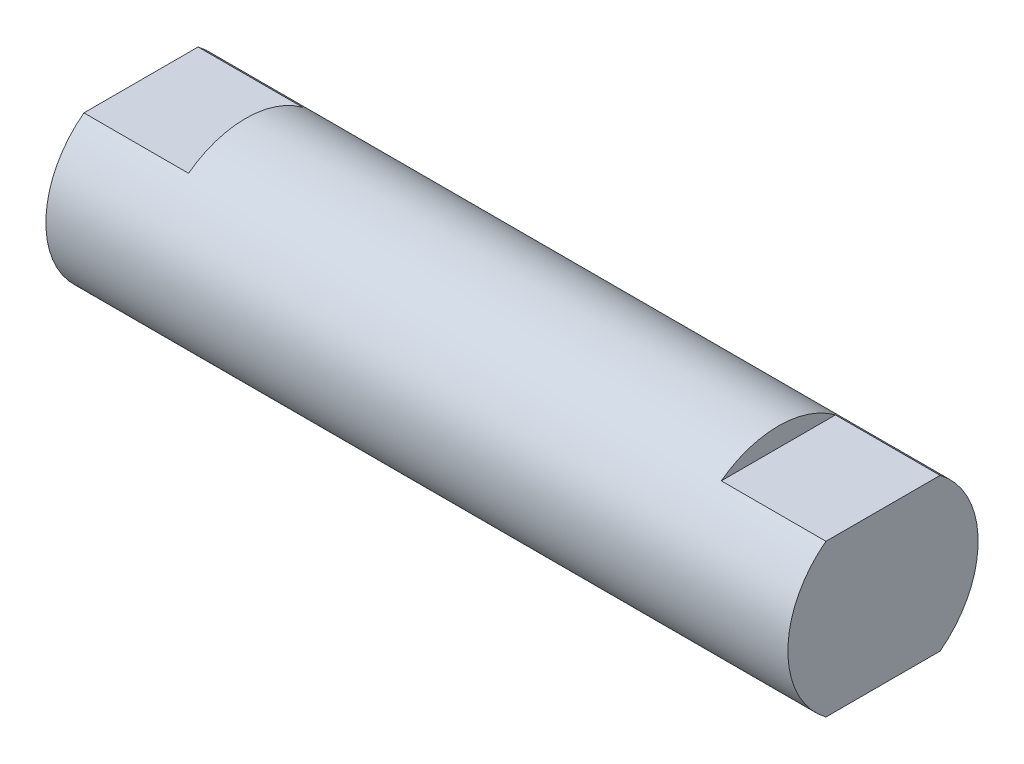
SolidWorks part; units mm, degrees
ref_plane "Front" through (0, 0, 0) normal (0, 0, 1) x (1, 0, 0)
ref_plane "Top" through (0, 0, 0) normal (0, 1, 0) x (1, 0, 0)
ref_plane "Right" through (0, 0, 0) normal (1, 0, 0) x (0, 0, -1)
ref_plane "Plane1" through (9.75, 0, 0) normal (1, 0, 0) x (0, 0, -1)
sketch "Sketch1" plane through (0, 0, 0) normal (1, 0, 0) x (0, 0, -1)
  circle A0 centre (0, 0) radius 2.5
  dimension "D1" = 5
extrude "Boss-Extrude1" add sketch "Sketch1" against normal mid plane 19.5
sketch "Sketch2" plane through (-9.75, 0, 0) normal (-1, 0, 0) x (0, 0, 1)
  line L0 (-1.5, 2) -> (1.5, 2)
  line L1 (1.5, -2) -> (-1.5, -2)
  line L2 (0, 0) -> (1.5, 0) construction
  arc A0 (1.5, 2) -> (-1.5, 2) centre (0, 0) ccw
  arc A1 (-1.5, -2) -> (1.5, -2) centre (0, 0) ccw
  circle A2 centre (0, 0) radius 2.5 construction
  dimension "D1" = 4
extrude "Cut-Extrude1" cut sketch "Sketch2" against normal blind 2.75
mirror "Mirror1" about plane through (0, 0, 0) normal (1, 0, 0) of "Cut-Extrude1"
